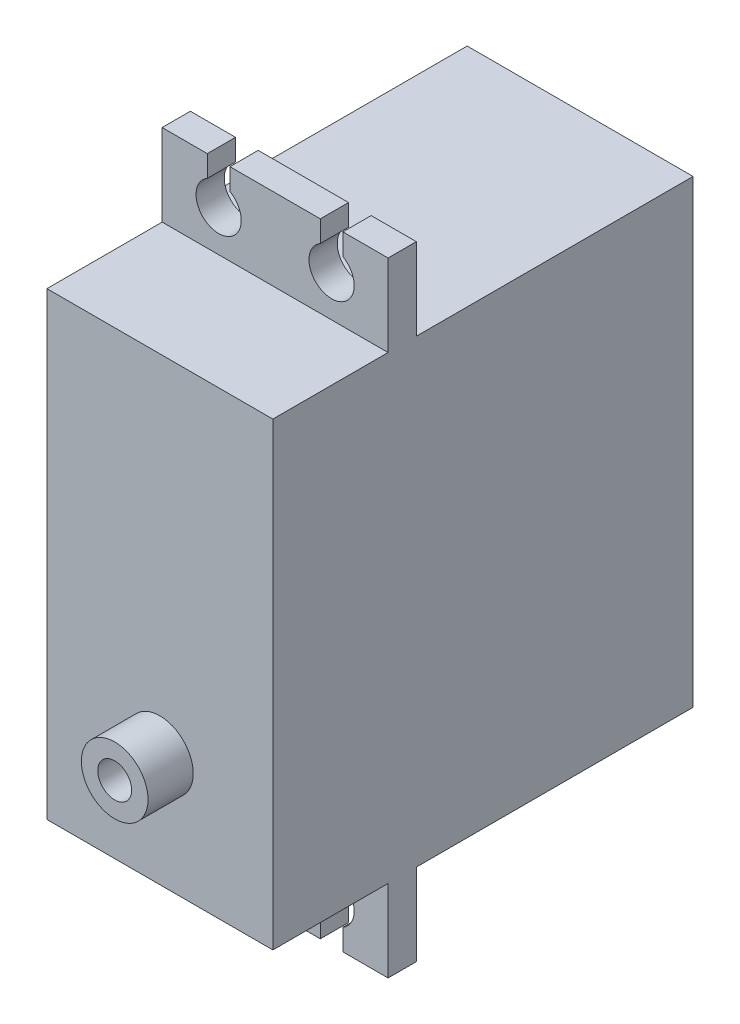
SolidWorks part; units mm, degrees
ref_plane "Front Plane" through (0, 0, 0) normal (1, 0, 0) x (0, 1, 0)
ref_plane "Top Plane" through (0, 0, 0) normal (0, 0, 1) x (0, 1, 0)
ref_plane "Right Plane" through (0, 0, 0) normal (0, 1, 0) x (-1, 0, 0)
sketch "Sketch1" plane through (0, 0, 0) normal (1, 0, 0) x (0, 1, 0)
  line L0 (-20.35, 5.9) -> (-27.6, 5.9)
  line L1 (20.35, 18.6) -> (-20.35, 18.6)
  line L2 (20.35, 18.6) -> (20.35, 8.4)
  line L3 (20.35, -18.6) -> (-20.35, -18.6)
  line L4 (-20.35, 18.6) -> (-20.35, 8.4)
  line L5 (20.35, 18.6) -> (-20.35, -18.6) construction
  line L6 (20.35, -18.6) -> (-20.35, 18.6) construction
  line L7 (-27.6, 5.9) -> (-27.6, 8.4)
  line L8 (-27.6, 8.4) -> (-20.35, 8.4)
  line L9 (-20.35, 5.9) -> (-20.35, -18.6)
  line L10 (0, -55) -> (0, 55) construction
  line L11 (20.35, 5.9) -> (27.6, 5.9)
  line L12 (27.6, 5.9) -> (27.6, 8.4)
  line L13 (27.6, 8.4) -> (20.35, 8.4)
  line L14 (20.35, 5.9) -> (20.35, -18.6)
  point P0 (0, 0)
  dimension "D1" = 40.7
  dimension "D2" = 37.2
  dimension "D3" = 24.5
  dimension "D4" = 2.5
  dimension "D5" = 7.25
extrude "Boss-Extrude1" add sketch "Sketch1" along normal mid plane 20
sketch "Sketch2" plane through (0, 0, 18.6) normal (0, 0, 1) x (1, 0, 0)
  line L0 (0, 20.35) -> (0, -20.35) construction
  line L1 (10, 20.35) -> (-10, 20.35) construction
  line L2 (10, -20.35) -> (-10, -20.35) construction
  line L3 (10, -20.35) -> (-10, -20.35) construction
  circle A0 centre (0, -10.35) radius 2.95
  circle A1 centre (0, -10.35) radius 1.5
  dimension "D1" = 5.9
  dimension "D3" = 3
  dimension "D2" = 10
sketch "Sketch4" plane through (0, 0, 8.4) normal (0, 0, 1) x (1, 0, 0)
  line L0 (0, -20.35) -> (0, -27.6) construction
  line L1 (10, -27.6) -> (-10, -27.6) construction
  line L2 (-6, -25.7071) -> (-6, -27.6)
  line L3 (-4, -27.6) -> (-4, -25.7071)
  line L4 (-6, -27.6) -> (-4, -27.6)
  line L5 (-10, -20.35) -> (-10, -27.6) construction
  line L6 (6, -27.6) -> (4, -27.6)
  line L7 (6, -25.7071) -> (6, -27.6)
  line L8 (4, -27.6) -> (4, -25.7071)
  arc A0 (-4, -25.7071) -> (-6, -25.7071) centre (-5, -23.975) ccw
  arc A1 (4, -25.7071) -> (6, -25.7071) centre (5, -23.975) cw
  point P8 (0, -23.975)
  dimension "D1" = 4
  dimension "D2" = 5
  dimension "D3" = 2
  dimension "D4" = 4
extrude "Cut-Extrude1" cut sketch "Sketch4" against normal through all
mirror "Mirror1" about plane through (0, 0, 0) normal (0, 1, 0) of "Cut-Extrude1"
sketch "Sketch5" plane through (0, -20.35, 0) normal (0, -1, 0) x (1, 0, 0)
  line L0 (10, -18.6) -> (-10, -18.6) construction
  line L1 (3, -16.6) -> (-3, -16.6)
  line L2 (3, -16.6) -> (3, -13.1)
  line L3 (3, -13.1) -> (-3, -13.1)
  line L4 (-3, -16.6) -> (-3, -13.1)
  line L5 (3, -16.6) -> (-3, -13.1) construction
  line L6 (3, -13.1) -> (-3, -16.6) construction
  point P0 (0, -14.85)
  dimension "D1" = 2
  dimension "D2" = 3.5
  dimension "D3" = 6
extrude "Boss-Extrude2" add sketch "Sketch5" along normal blind 6
extrude "Boss-Extrude3" add sketch "Sketch2" along normal blind 4
